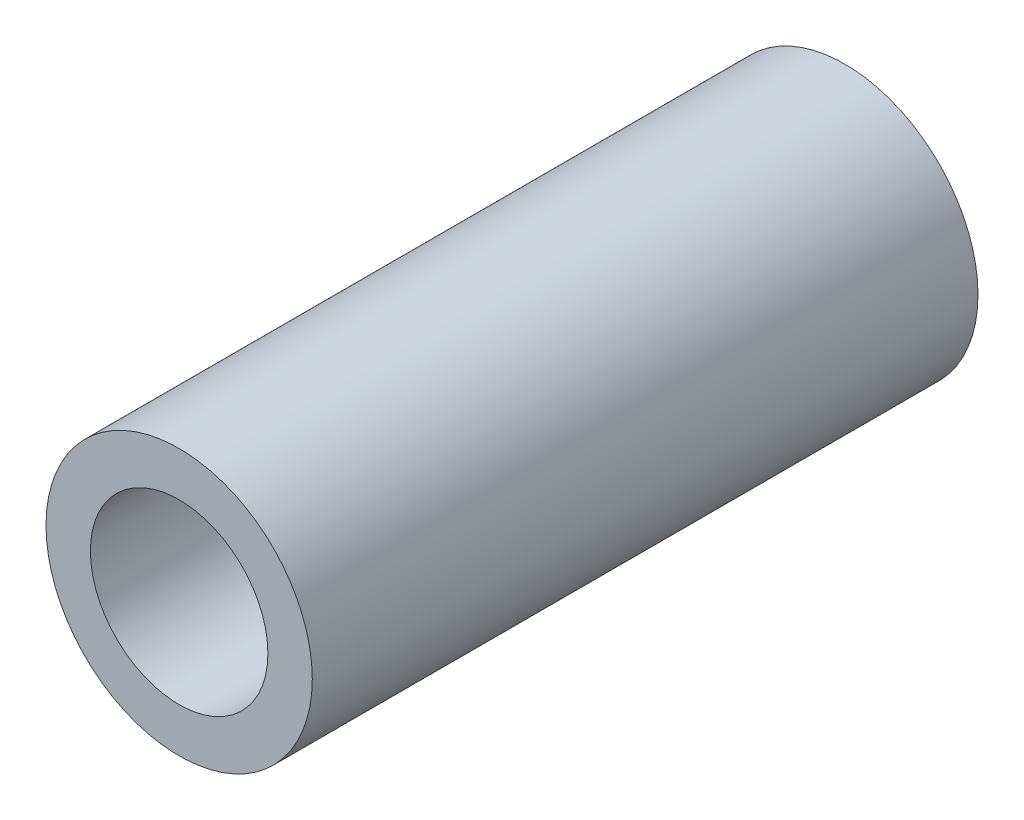
SolidWorks part; units mm, degrees
ref_plane "Front Plane" through (0, 0, 0) normal (0, 0, 1) x (1, 0, 0)
ref_plane "Top Plane" through (0, 0, 0) normal (0, 1, 0) x (1, 0, 0)
ref_plane "Right Plane" through (0, 0, 0) normal (1, 0, 0) x (0, 0, -1)
sketch "Sketch1" plane through (0, 0, 0) normal (0, 0, 1) x (1, 0, 0)
  circle A0 centre (0, 0) radius 2
  circle A1 centre (0, 0) radius 3
extrude "Boss-Extrude1" add sketch "Sketch1" along normal blind 15
